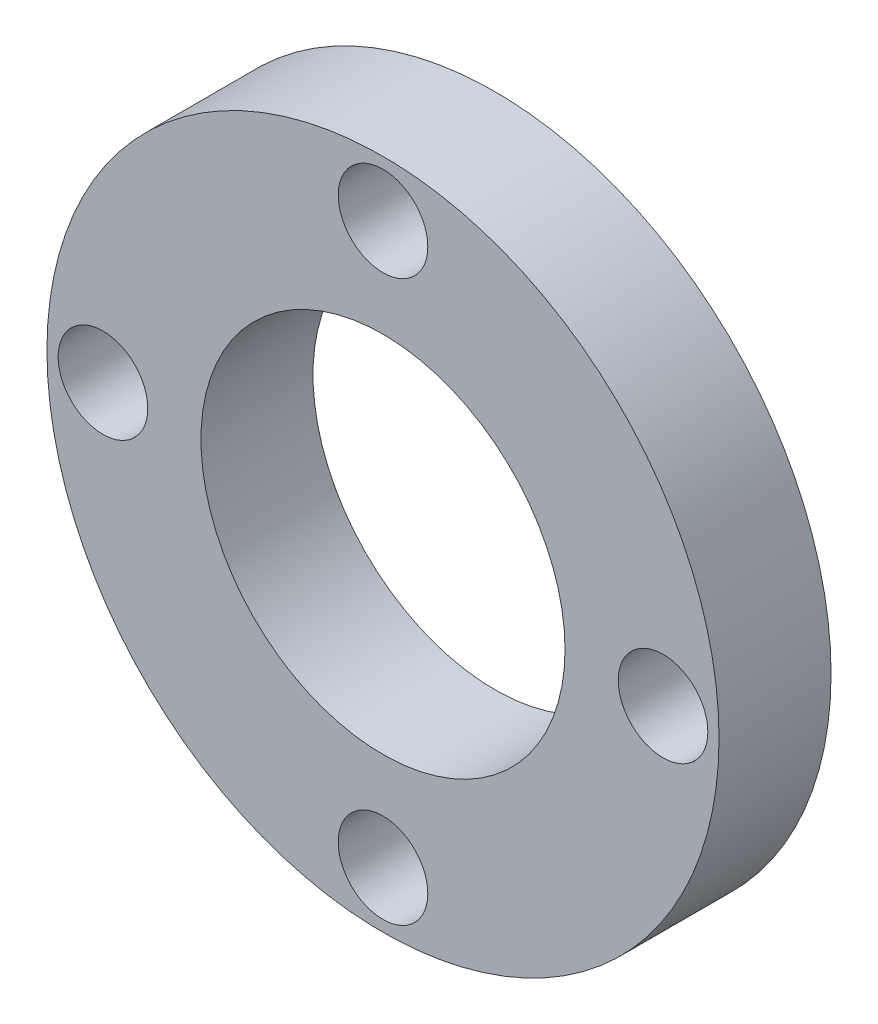
SolidWorks part; units mm, degrees
ref_plane "前视基准面" through (0, 0, 0) normal (0, 0, 1) x (1, 0, 0)
ref_plane "上视基准面" through (0, 0, 0) normal (0, 1, 0) x (1, 0, 0)
ref_plane "右视基准面" through (0, 0, 0) normal (1, 0, 0) x (0, 0, -1)
sketch "草图1" plane through (0, 0, 0) normal (0, 0, 1) x (1, 0, 0)
  circle A0 centre (0, 0) radius 6.5
  circle A1 centre (0, 0) radius 12
  circle A2 centre (0, 0) radius 10 construction
  circle A3 centre (0, 10) radius 1.6
  circle A4 centre (10, 0) radius 1.6
  circle A5 centre (0, -10) radius 1.6
  circle A6 centre (-10, 0) radius 1.6
  point P16 (0, 0)
  dimension "D1" = 3.2
  dimension "D2" = 13
  dimension "D3" = 20
  dimension "D4" = 24
  dimension "D5" = 4
extrude "凸台-拉伸1" add sketch "草图1" along normal blind 4
